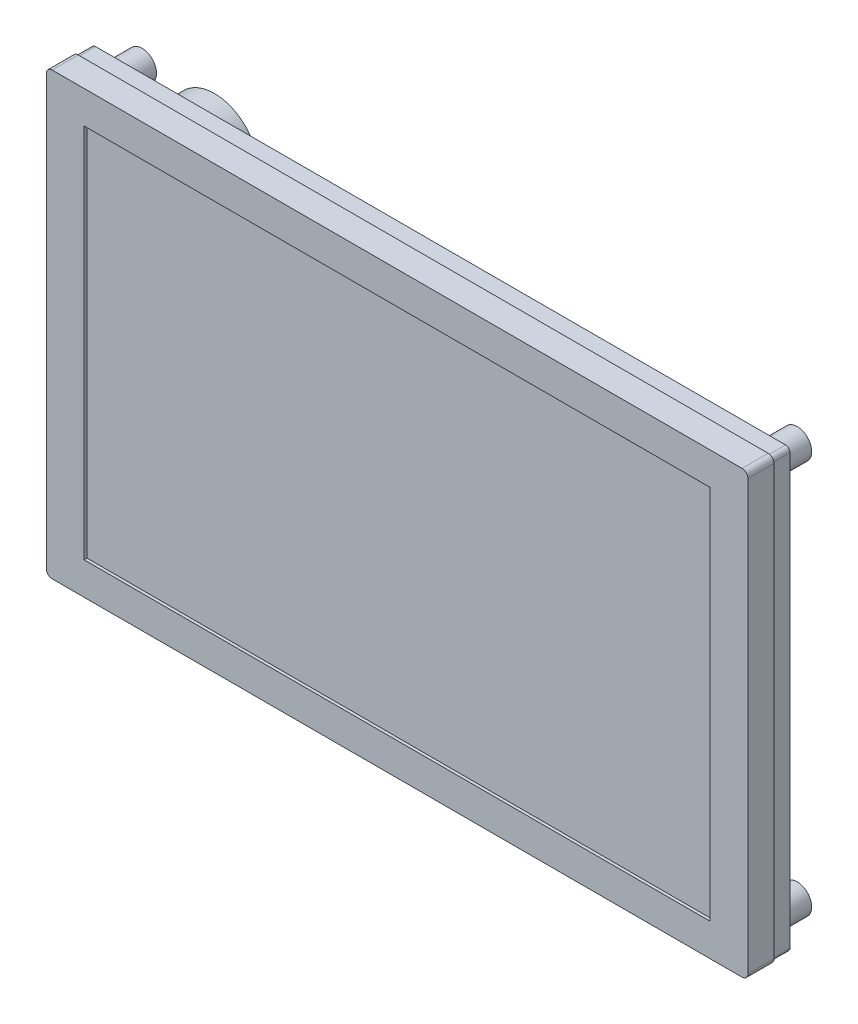
SolidWorks part; units mm, degrees
ref_plane "Front" through (0, 0, 0) normal (0, 0, 1) x (1, 0, 0)
ref_plane "Top" through (0, 0, 0) normal (0, 1, 0) x (1, 0, 0)
ref_plane "Right" through (0, 0, 0) normal (1, 0, 0) x (0, 0, -1)
sketch "Esquisse1" plane through (0, 0, 0) normal (0, 0, 1) x (1, 0, 0)
  line L1 (-60.5, 38) -> (60.5, 38)
  line L2 (-60.5, 38) -> (-60.5, -38)
  line L3 (-60.5, -38) -> (60.5, -38)
  line L4 (60.5, 38) -> (60.5, -38)
  point P4 (-60.5, 0)
  point P5 (0, 38)
  dimension "D1" = 121
  dimension "D2" = 76
extrude "Boss.-Extru.1" add sketch "Esquisse1" against normal blind 7.5
sketch "Esquisse2" plane through (0, 0, -7.5) normal (0, 0, -1) x (-1, 0, 0)
  line L0 (-60.5, 38) -> (60.5, 38) construction
  line L1 (-60.5, -38) -> (-60.5, 38) construction
  line L2 (60.5, 38) -> (60.5, -38) construction
  line L3 (60.5, -38) -> (-60.5, -38) construction
  circle A0 centre (-56.5, 34) radius 2.5
  circle A1 centre (-56.5, -34) radius 2.5
  circle A2 centre (-29, 24.5) radius 2.5
  circle A3 centre (-29, -24.5) radius 2.5
  circle A4 centre (29, 24.5) radius 2.5
  circle A5 centre (29, -24.5) radius 2.5
  circle A6 centre (56.5, 34) radius 2.5
  circle A7 centre (56.5, -34) radius 2.5
  dimension "D1" = 113
  dimension "D2" = 58
  dimension "D3" = 68
  dimension "D4" = 4
  dimension "D5" = 4
  dimension "D6" = 4
  dimension "D7" = 4
  dimension "D8" = 5
  dimension "D9" = 49
  dimension "D10" = 29
  dimension "D11" = 24.5
extrude "Extru.-Mince1" add sketch "Esquisse2" along normal blind 5 separate body thin thin type one direction reverse wall 1.25
fillet "Congé1" radius 1 4 edges at (-60.5, -38, -3.75) (60.5, -38, -3.75) (-60.5, 38, -3.75) (60.5, 38, -3.75)
sketch "Esquisse3" plane through (0, 0, 0) normal (0, 0, 1) x (1, 0, 0)
  line L1 (-54, -32.4) -> (54, -32.4)
  line L2 (-54, -32.4) -> (-54, 32.4)
  line L3 (-54, 32.4) -> (54, 32.4)
  line L4 (54, -32.4) -> (54, 32.4)
  line L5 (0, 32.4) -> (0, -32.4) construction
  line L6 (-54, 0) -> (54, 0) construction
  point P0 (0, 0)
  dimension "D1" = 108
  dimension "D2" = 64.8
extrude "Enlèv. mat.-Extru.1" cut sketch "Esquisse3" against normal blind 0.5
sketch "Esquisse4" plane through (0, 0, -7.5) normal (0, 0, -1) x (-1, 0, 0)
  line L4 (-59.5, -38) -> (59.5, -38)
  line L5 (60.5, -37) -> (60.5, 37)
  line L6 (59.5, 38) -> (-59.5, 38)
  line L7 (-60.5, 37) -> (-60.5, -37)
  line L8 (-59.5, -38) -> (59.5, -38)
  line L9 (60.5, -37) -> (60.5, 37)
  line L10 (59.5, 38) -> (-59.5, 38)
  line L11 (-60.5, 37) -> (-60.5, -37)
  arc A4 (59.5, -38) -> (60.5, -37) centre (59.5, -37) ccw
  arc A5 (60.5, 37) -> (59.5, 38) centre (59.5, 37) ccw
  arc A6 (-59.5, 38) -> (-60.5, 37) centre (-59.5, 37) ccw
  arc A7 (-60.5, -37) -> (-59.5, -38) centre (-59.5, -37) ccw
  arc A8 (59.5, -38) -> (60.5, -37) centre (59.5, -37) ccw
  arc A9 (60.5, 37) -> (59.5, 38) centre (59.5, 37) ccw
  arc A10 (-59.5, 38) -> (-60.5, 37) centre (-59.5, 37) ccw
  arc A11 (-60.5, -37) -> (-59.5, -38) centre (-59.5, -37) ccw
  dimension "D1" = 0
extrude "Enlèv. de mat.-Extru.-Mince1" cut sketch "Esquisse4" against normal blind 3 thin thin type one direction reverse wall 0.25
sketch "Esquisse5" plane through (0, 0, -7.5) normal (0, 0, -1) x (-1, 0, 0)
  line L0 (59.5, 38) -> (-59.5, 38) construction
  line L1 (60.5, -37) -> (60.5, 37) construction
  circle A0 centre (42.5, 30) radius 7.5
  dimension "D1" = 15
  dimension "D2" = 8
  dimension "D3" = 18
extrude "Boss.-Extru.2" add sketch "Esquisse5" along normal blind 3.5
sketch "Esquisse6" plane through (0, 0, -7.5) normal (0, 0, -1) x (-1, 0, 0)
  line L0 (60.5, -37) -> (60.5, 37) construction
  line L1 (43, 11) -> (48, 11)
  line L2 (43, 11) -> (43, -11)
  line L3 (43, -11) -> (48, -11)
  line L4 (48, 11) -> (48, -11)
  point P7 (43, 0)
  dimension "D1" = 5
  dimension "D2" = 22
  dimension "D3" = 12.5
extrude "Boss.-Extru.3" add sketch "Esquisse6" along normal blind 3
sketch "Esquisse7" plane through (-48, 0, 0) normal (-1, 0, 0) x (0, 0, 1)
  line L0 (-10.5, -11) -> (-10.5, 11) construction
  line L1 (-9.5, 8) -> (-9, 8)
  line L2 (-9.5, 8) -> (-9.5, -8)
  line L3 (-9.5, -8) -> (-9, -8)
  line L4 (-9, 8) -> (-9, -8)
  point P4 (-9.5, 0)
  dimension "D1" = 1
  dimension "D2" = 0.5
  dimension "D3" = 16
sketch "Esquisse8" plane through (0, 0, 0) normal (0, 1, 0) x (1, 0, 0)
  line L0 (-48, 9.5) -> (-49, 9.5)
  arc A0 (-49, 9.5) -> (-53.3043, 13.8043) centre (-49, 13.8043) cw
  arc A1 (-53.3043, 13.8043) -> (-28, 18) centre (-40.3043, 13.8043) cw
  dimension "D1" = 18
  dimension "D3" = 13
  dimension "D2" = 28
  dimension "D5" = 1
sweep "Balayage1" add profiles "Esquisse7" path "Esquisse8"
